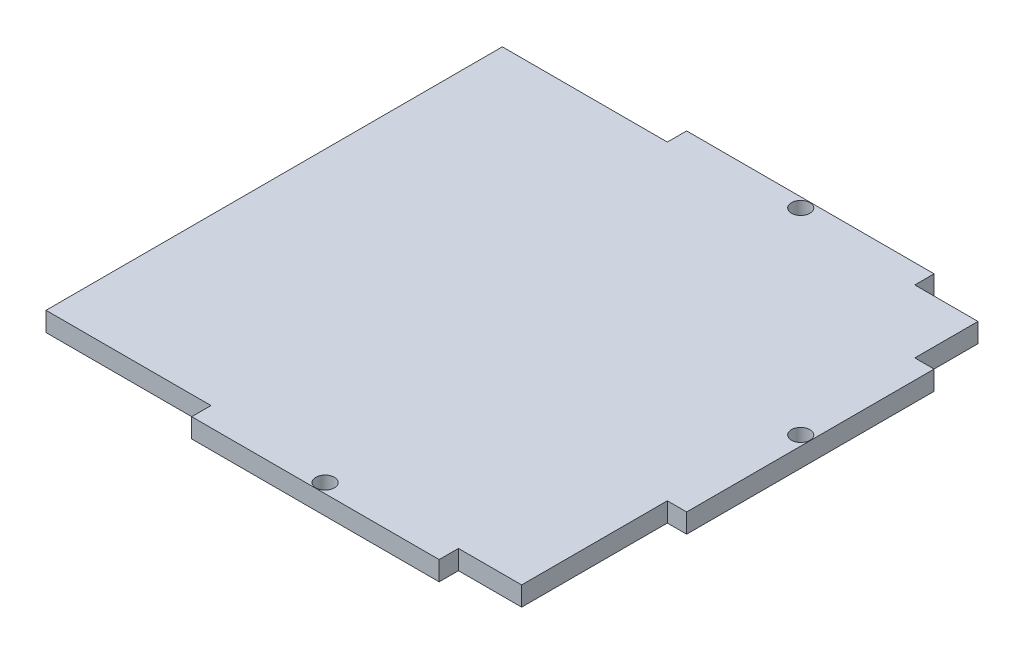
SolidWorks part; units mm, degrees
ref_plane "Front Plane" through (0, 0, 0) normal (0, 0, 1) x (1, 0, 0)
ref_plane "Top Plane" through (0, 0, 0) normal (0, 1, 0) x (1, 0, 0)
ref_plane "Right Plane" through (0, 0, 0) normal (1, 0, 0) x (0, 0, -1)
sketch "Sketch1" plane through (0, 0, 0) normal (0, 1, 0) x (1, 0, 0)
  line L1 (-38.1, -38.1) -> (38.1, -38.1)
  line L2 (-38.1, -38.1) -> (-38.1, 38.1)
  line L3 (-38.1, 38.1) -> (38.1, 38.1)
  line L4 (38.1, -38.1) -> (38.1, 38.1)
  line L5 (-38.1, -38.1) -> (38.1, 38.1) construction
  line L6 (-38.1, 38.1) -> (38.1, -38.1) construction
  point P0 (0, 0)
  dimension "D1" = 76.2
  dimension "D2" = 76.2
extrude "Boss-Extrude1" add sketch "Sketch1" along normal blind 2.9718
sketch "Sketch2" plane through (0, 2.9718, 0) normal (0, 1, 0) x (1, 0, 0)
  line L0 (-38.1, -38.1) -> (38.1, -38.1) construction
  line L1 (-38.1, 38.1) -> (-12.7, 38.1)
  line L2 (-38.1, 38.1) -> (-38.1, 35.1282)
  line L3 (-38.1, 35.1282) -> (-12.7, 35.1282)
  line L4 (-12.7, 38.1) -> (-12.7, 35.1282)
  line L5 (38.1, 38.1) -> (25.4, 38.1)
  line L6 (38.1, 38.1) -> (38.1, 35.1282)
  line L7 (38.1, 35.1282) -> (25.4, 35.1282)
  line L8 (25.4, 38.1) -> (25.4, 35.1282)
  line L9 (38.1, 38.1) -> (35.1282, 38.1)
  line L10 (38.1, 38.1) -> (38.1, 25.4)
  line L11 (38.1, 25.4) -> (35.1282, 25.4)
  line L12 (35.1282, 38.1) -> (35.1282, 25.4)
  line L13 (38.1, -38.1) -> (35.1282, -38.1)
  line L14 (38.1, -38.1) -> (38.1, -12.7)
  line L15 (38.1, -12.7) -> (35.1282, -12.7)
  line L16 (35.1282, -38.1) -> (35.1282, -12.7)
  line L17 (38.1, -38.1) -> (38.1, 38.1) construction
  line L18 (38.1, 38.1) -> (-38.1, 38.1) construction
  line L19 (-39.2339, 0) -> (38.1, 0) construction
  line L21 (38.1, -38.1) -> (25.4, -38.1)
  line L22 (38.1, -38.1) -> (38.1, -35.1282)
  line L23 (38.1, -35.1282) -> (25.4, -35.1282)
  line L24 (25.4, -38.1) -> (25.4, -35.1282)
  line L25 (-38.1, -38.1) -> (-12.7, -38.1)
  line L26 (-38.1, -38.1) -> (-38.1, -35.1282)
  line L27 (-38.1, -35.1282) -> (-12.7, -35.1282)
  line L28 (-12.7, -38.1) -> (-12.7, -35.1282)
  circle A0 centre (6.35, 36.6141) radius 1.4224
  circle A1 centre (36.6141, 6.35) radius 1.4224
  circle A2 centre (6.35, -36.6141) radius 1.4224
  line M16 (38.1, 38.1) -> (-38.1, 38.1)
  line M17 (-38.1, 38.1) -> (-38.1, -38.1)
  dimension "D9" = 2.8448
  dimension "D10" = 2.8448
  dimension "D16" = 2.8448
  dimension "D1" = 2.9718
  dimension "D2" = 2.9718
  dimension "D3" = 2.9718
  dimension "D4" = 2.9718
  dimension "D5" = 38.1
  dimension "D6" = 38.1
  dimension "D7" = 12.7
  dimension "D8" = 12.7
  dimension "D11" = 1.4859
  dimension "D12" = 1.4859
  dimension "D13" = 31.75
  dimension "D14" = 31.75
  dimension "D15" = 1.4859
  dimension "D17" = 12.7
  dimension "D18" = 2.9718
  dimension "D19" = 2.9718
  dimension "D20" = 38.1
extrude "Cut-Extrude1" cut sketch "Sketch2" against normal through all contours L4 L3 M16 M17 | L5 L8 L7 L6 | L10 L11 L12 L9 | L14 L15 L16 L13 | A1 | A0 | L22 L21 L24 L23 | A2 | L26 L25 L28 L27
